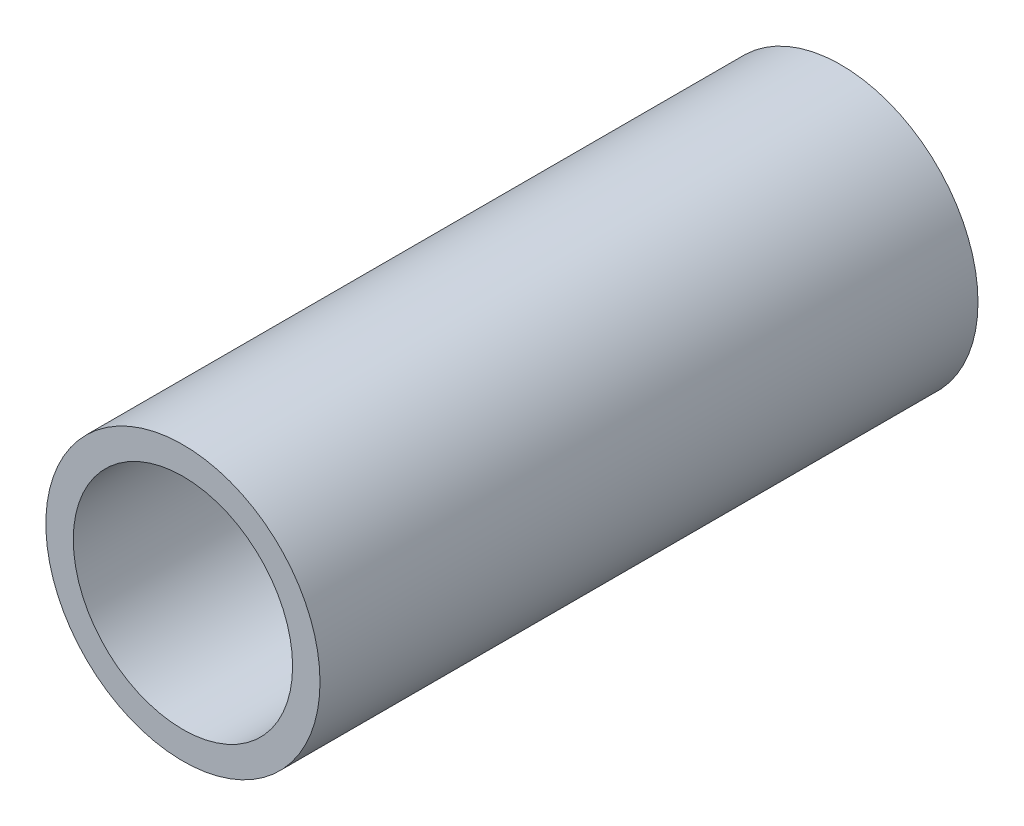
SolidWorks part; units mm, degrees
ref_plane "Front Plane" through (0, 0, 0) normal (0, 0, 1) x (1, 0, 0)
ref_plane "Top Plane" through (0, 0, 0) normal (0, 1, 0) x (1, 0, 0)
ref_plane "Right Plane" through (0, 0, 0) normal (1, 0, 0) x (0, 0, -1)
sketch "Sketch1" plane through (0, 0, 0) normal (0, 0, 1) x (1, 0, 0)
  circle A0 centre (0, 0) radius 25
  dimension "D1" = 50
extrude "Boss-Extrude1" add sketch "Sketch1" along normal blind 120 contours A0
sketch "Sketch2" plane through (0, 0, 120) normal (0, 0, 1) x (1, 0, 0)
  circle A0 centre (0, 0) radius 20
  dimension "D1" = 40
extrude "Cut-Extrude1" cut sketch "Sketch2" against normal through all
